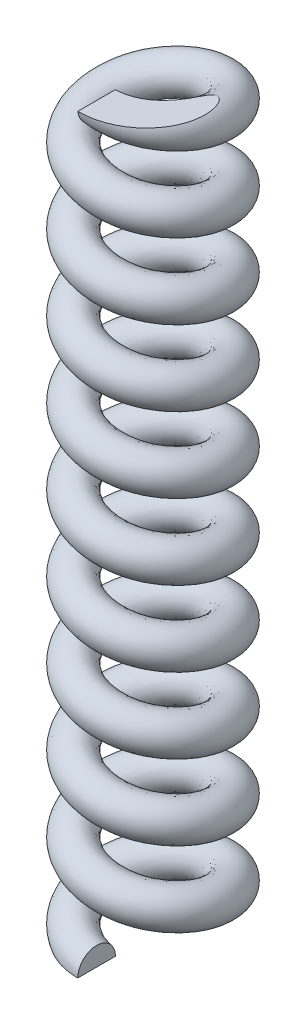
SolidWorks part; units mm, degrees
material "Stal nierdzewna (ferrytyczna)"
ref_plane "Front Plane" through (0, 0, 0) normal (0, 0, 1) x (1, 0, 0)
ref_plane "Top Plane" through (0, 0, 0) normal (0, 1, 0) x (1, 0, 0)
ref_plane "Right Plane" through (0, 0, 0) normal (1, 0, 0) x (0, 0, -1)
sketch "Szkic1" plane through (0, 0, 0) normal (0, 1, 0) x (1, 0, 0)
  circle A0 centre (0, 0) radius 0.75
curve "Helisa/Spirala1" pitch 1 height 10 turns 10
sketch "Szkic4" plane through (0, 0, 0) normal (1, 0, 0) x (0, 0, -1)
  circle A0 centre (-0.75, 0) radius 0.25
  spline S0 degree 3 poles (-0.75, 0) (-0.75, 0.0207) (-0.7109, 0.0626) (-0.5441, 0.125) (-0.2945, 0.1875) (0, 0.25) (0.2945, 0.3125) (0.5441, 0.375) (0.7109, 0.4375) (0.7695, 0.5) (0.7109, 0.5625) (0.5441, 0.625) (0.2945, 0.6875) (0, 0.75) (-0.2945, 0.8125) (-0.5441, 0.875) (-0.7109, 0.9375) (-0.7695, 1) (-0.7109, 1.0625) (-0.5441, 1.125) (-0.2945, 1.1875) (0, 1.25) (0.2945, 1.3125) (0.5441, 1.375) (0.7109, 1.4375) (0.7695, 1.5) (0.7109, 1.5625) (0.5441, 1.625) (0.2945, 1.6875) (0, 1.75) (-0.2945, 1.8125) (-0.5441, 1.875) (-0.7109, 1.9375) (-0.7695, 2) (-0.7109, 2.0625) (-0.5441, 2.125) (-0.2945, 2.1875) (0, 2.25) (0.2945, 2.3125) (0.5441, 2.375) (0.7109, 2.4375) (0.7695, 2.5) (0.7109, 2.5625) (0.5441, 2.625) (0.2945, 2.6875) (0, 2.75) (-0.2945, 2.8125) (-0.5441, 2.875) (-0.7109, 2.9375) (-0.7695, 3) (-0.7109, 3.0625) (-0.5441, 3.125) (-0.2945, 3.1875) (0, 3.25) (0.2945, 3.3125) (0.5441, 3.375) (0.7109, 3.4375) (0.7695, 3.5) (0.7109, 3.5625) (0.5441, 3.625) (0.2945, 3.6875) (0, 3.75) (-0.2945, 3.8125) (-0.5441, 3.875) (-0.7109, 3.9375) (-0.7695, 4) (-0.7109, 4.0625) (-0.5441, 4.125) (-0.2945, 4.1875) (0, 4.25) (0.2945, 4.3125) (0.5441, 4.375) (0.7109, 4.4375) (0.7695, 4.5) (0.7109, 4.5625) (0.5441, 4.625) (0.2945, 4.6875) (0, 4.75) (-0.2945, 4.8125) (-0.5441, 4.875) (-0.7109, 4.9375) (-0.7695, 5) (-0.7109, 5.0625) (-0.5441, 5.125) (-0.2945, 5.1875) (0, 5.25) (0.2945, 5.3125) (0.5441, 5.375) (0.7109, 5.4375) (0.7695, 5.5) (0.7109, 5.5625) (0.5441, 5.625) (0.2945, 5.6875) (0, 5.75) (-0.2945, 5.8125) (-0.5441, 5.875) (-0.7109, 5.9375) (-0.7695, 6) (-0.7109, 6.0625) (-0.5441, 6.125) (-0.2945, 6.1875) (0, 6.25) (0.2945, 6.3125) (0.5441, 6.375) (0.7109, 6.4375) (0.7695, 6.5) (0.7109, 6.5625) (0.5441, 6.625) (0.2945, 6.6875) (0, 6.75) (-0.2945, 6.8125) (-0.5441, 6.875) (-0.7109, 6.9375) (-0.7695, 7) (-0.7109, 7.0625) (-0.5441, 7.125) (-0.2945, 7.1875) (0, 7.25) (0.2945, 7.3125) (0.5441, 7.375) (0.7109, 7.4375) (0.7695, 7.5) (0.7109, 7.5625) (0.5441, 7.625) (0.2945, 7.6875) (0, 7.75) (-0.2945, 7.8125) (-0.5441, 7.875) (-0.7109, 7.9375) (-0.7695, 8) (-0.7109, 8.0625) (-0.5441, 8.125) (-0.2945, 8.1875) (0, 8.25) (0.2945, 8.3125) (0.5441, 8.375) (0.7109, 8.4375) (0.7695, 8.5) (0.7109, 8.5625) (0.5441, 8.625) (0.2945, 8.6875) (0, 8.75) (-0.2945, 8.8125) (-0.5441, 8.875) (-0.7109, 8.9375) (-0.7695, 9) (-0.7109, 9.0625) (-0.5441, 9.125) (-0.2945, 9.1875) (0, 9.25) (0.2945, 9.3125) (0.5441, 9.375) (0.7109, 9.4375) (0.7695, 9.5) (0.7109, 9.5625) (0.5441, 9.625) (0.2945, 9.6875) (0, 9.75) (-0.2945, 9.8125) (-0.5441, 9.875) (-0.7109, 9.9374) (-0.75, 9.9793) (-0.75, 10) knots 0 0 0 0 0.00625 0.0125 0.01875 0.025 0.03125 0.0375 0.04375 0.05 0.05625 0.0625 0.06875 0.075 0.08125 0.0875 0.09375 0.1 0.10625 0.1125 0.11875 0.125 0.13125 0.1375 0.14375 0.15 0.15625 0.1625 0.16875 0.175 0.18125 0.1875 0.19375 0.2 0.20625 0.2125 0.21875 0.225 0.23125 0.2375 0.24375 0.25 0.25625 0.2625 0.26875 0.275 0.28125 0.2875 0.29375 0.3 0.30625 0.3125 0.31875 0.325 0.33125 0.3375 0.34375 0.35 0.35625 0.3625 0.36875 0.375 0.38125 0.3875 0.39375 0.4 0.40625 0.4125 0.41875 0.425 0.43125 0.4375 0.44375 0.45 0.45625 0.4625 0.46875 0.475 0.48125 0.4875 0.49375 0.5 0.50625 0.5125 0.51875 0.525 0.53125 0.5375 0.54375 0.55 0.55625 0.5625 0.56875 0.575 0.58125 0.5875 0.59375 0.6 0.60625 0.6125 0.61875 0.625 0.63125 0.6375 0.64375 0.65 0.65625 0.6625 0.66875 0.675 0.68125 0.6875 0.69375 0.7 0.70625 0.7125 0.71875 0.725 0.73125 0.7375 0.74375 0.75 0.75625 0.7625 0.76875 0.775 0.78125 0.7875 0.79375 0.8 0.80625 0.8125 0.81875 0.825 0.83125 0.8375 0.84375 0.85 0.85625 0.8625 0.86875 0.875 0.88125 0.8875 0.89375 0.9 0.90625 0.9125 0.91875 0.925 0.93125 0.9375 0.94375 0.95 0.95625 0.9625 0.96875 0.975 0.98125 0.9875 0.99375 1 1 1 1 construction
sweep "Wyciągnięcie po ścieżce1" add profiles "Szkic4" path "Helisa/Spirala1"
ref_plane "Płaszczyzna1" through (0, 9.9785, 0) normal (0, 1, 0) x (1, 0, 0)
other "Cięcie powierzchnią3"
other "Cięcie powierzchnią4"
